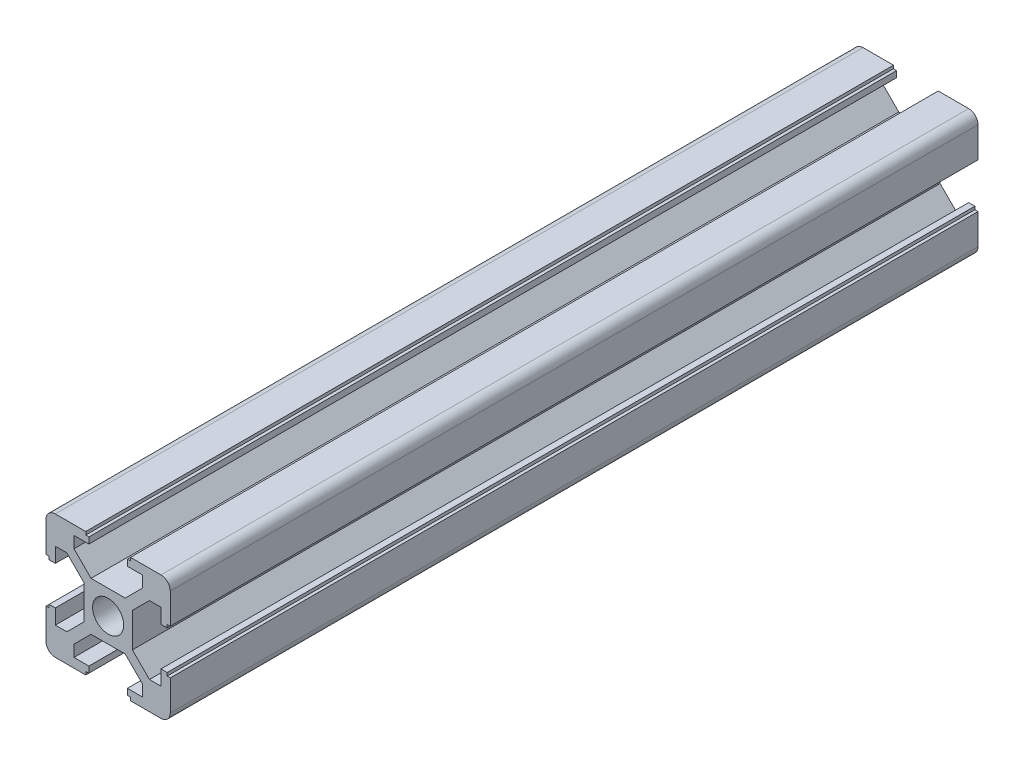
SolidWorks part; units mm, degrees
ref_plane "前视基准面" through (0, 0, 0) normal (0, 0, 1) x (1, 0, 0)
ref_plane "上视基准面" through (0, 0, 0) normal (0, 1, 0) x (1, 0, 0)
ref_plane "右视基准面" through (0, 0, 0) normal (1, 0, 0) x (0, 0, -1)
other "Configuration Table"
sketch "草图2" plane through (0, 0, 0) normal (0, 0, 1) x (1, 0, 0)
  line L0 (-3.6, 10) -> (-3.6, 9.5)
  line L1 (-3.6, 9.5) -> (-3.1, 9.5)
  line L2 (-3.1, 9.5) -> (-3.1, 8.5)
  line L3 (-3.1, 8.5) -> (-5.5, 8.5)
  line L4 (-8.5, -10) -> (-3.6, -10)
  line L5 (-10, -8.5) -> (-10, -3.6)
  line L6 (8.5, 10) -> (3.6, 10)
  line L7 (10, 8.5) -> (10, 3.6)
  line L8 (0, 14.8756) -> (0, 0) construction
  line L9 (0, 0) -> (14.1675, 0) construction
  line L10 (-5.5, 8.5) -> (-5.5, 6.65)
  line L11 (-5.5, 6.65) -> (-2.75, 3.9)
  line L12 (-2.75, 3.9) -> (2.75, 3.9)
  line L13 (5.5, 6.65) -> (2.75, 3.9)
  line L14 (5.5, 8.5) -> (5.5, 6.65)
  line L15 (3.1, 8.5) -> (5.5, 8.5)
  line L16 (3.1, 9.5) -> (3.1, 8.5)
  line L17 (3.6, 9.5) -> (3.1, 9.5)
  line L18 (3.6, 10) -> (3.6, 9.5)
  line L19 (-3.6, 10) -> (-8.5, 10)
  line L20 (10, 3.6) -> (9.5, 3.6)
  line L21 (9.5, 3.6) -> (9.5, 3.1)
  line L22 (9.5, 3.1) -> (8.5, 3.1)
  line L23 (8.5, 3.1) -> (8.5, 5.5)
  line L24 (8.5, 5.5) -> (6.65, 5.5)
  line L25 (6.65, 5.5) -> (3.9, 2.75)
  line L26 (3.9, 2.75) -> (3.9, -2.75)
  line L27 (6.65, -5.5) -> (3.9, -2.75)
  line L28 (8.5, -5.5) -> (6.65, -5.5)
  line L29 (8.5, -3.1) -> (8.5, -5.5)
  line L30 (9.5, -3.1) -> (8.5, -3.1)
  line L31 (9.5, -3.6) -> (9.5, -3.1)
  line L32 (10, -3.6) -> (9.5, -3.6)
  line L33 (3.6, -10) -> (3.6, -9.5)
  line L34 (3.6, -9.5) -> (3.1, -9.5)
  line L35 (3.1, -9.5) -> (3.1, -8.5)
  line L36 (3.1, -8.5) -> (5.5, -8.5)
  line L37 (5.5, -8.5) -> (5.5, -6.65)
  line L38 (5.5, -6.65) -> (2.75, -3.9)
  line L39 (2.75, -3.9) -> (-2.75, -3.9)
  line L40 (-5.5, -6.65) -> (-2.75, -3.9)
  line L41 (-5.5, -8.5) -> (-5.5, -6.65)
  line L42 (-3.1, -8.5) -> (-5.5, -8.5)
  line L43 (-3.1, -9.5) -> (-3.1, -8.5)
  line L44 (-3.6, -9.5) -> (-3.1, -9.5)
  line L45 (-3.6, -10) -> (-3.6, -9.5)
  line L46 (-10, -3.6) -> (-9.5, -3.6)
  line L47 (-9.5, -3.6) -> (-9.5, -3.1)
  line L48 (-9.5, -3.1) -> (-8.5, -3.1)
  line L49 (-8.5, -3.1) -> (-8.5, -5.5)
  line L50 (-8.5, -5.5) -> (-6.65, -5.5)
  line L51 (-6.65, -5.5) -> (-3.9, -2.75)
  line L52 (-3.9, -2.75) -> (-3.9, 2.75)
  line L53 (-6.65, 5.5) -> (-3.9, 2.75)
  line L54 (-8.5, 5.5) -> (-6.65, 5.5)
  line L55 (-8.5, 3.1) -> (-8.5, 5.5)
  line L56 (-9.5, 3.1) -> (-8.5, 3.1)
  line L57 (-9.5, 3.6) -> (-9.5, 3.1)
  line L58 (-10, 3.6) -> (-9.5, 3.6)
  line L59 (3.6, -10) -> (8.5, -10)
  line L60 (-10, 3.6) -> (-10, 8.5)
  line L61 (10, -3.6) -> (10, -8.5)
  circle A0 centre (0, 0) radius 2.5
  arc A1 (-10, 8.5) -> (-8.5, 10) centre (-8.5, 8.5) cw
  arc A2 (10, 8.5) -> (8.5, 10) centre (8.5, 8.5) ccw
  arc A3 (-8.5, -10) -> (-10, -8.5) centre (-8.5, -8.5) cw
  arc A4 (8.5, -10) -> (10, -8.5) centre (8.5, -8.5) ccw
  point P0 (-10, 0)
  point P1 (10, 0)
  point P2 (0, 10)
  point P3 (0, -10)
  point P4 (0, 0)
  point P5 (-10, -10)
  point P6 (10, -10)
  point P7 (10, 10)
  point P8 (-10, 10)
  point P36 (-10, 10)
  point P39 (10, 10)
  dimension "D1" = 11
  dimension "D2" = 20
  dimension "D3" = 6.2
  dimension "D4" = 7.2
  dimension "D5" = 6.1
  dimension "D6" = 5
  dimension "D7" = 1.5
  dimension "D8" = 45
  dimension "D9" = 0.5
  dimension "D10" = 1
  dimension "D11" = 5.5
extrude "凸台-拉伸1" add sketch "草图2" along normal blind 130
